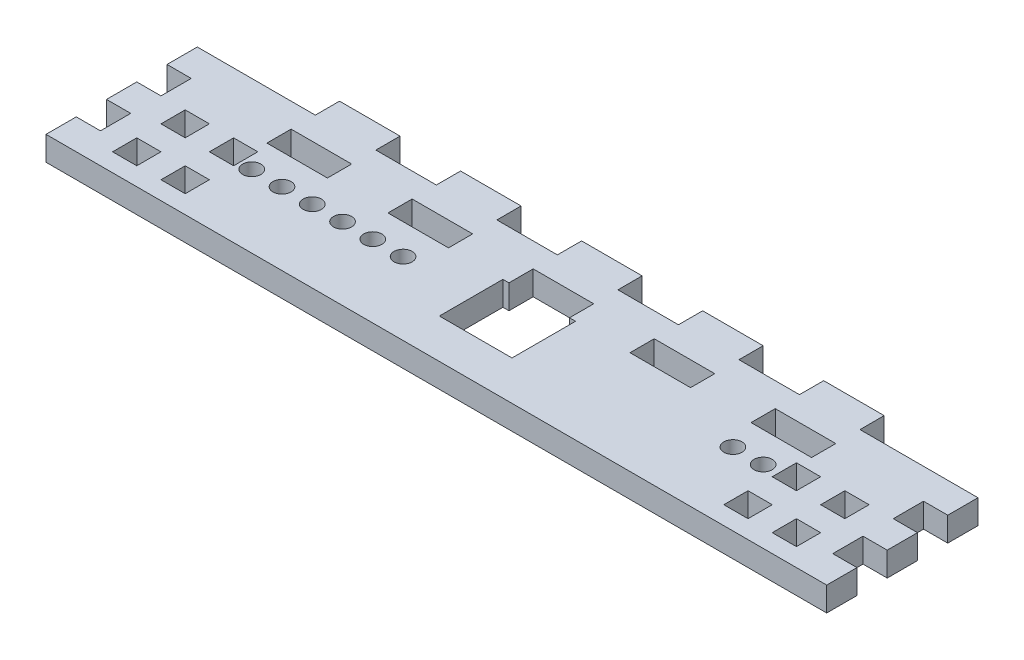
SolidWorks part; units mm, degrees
material "Maple"
ref_plane "Front Plane" through (0, 0, 0) normal (0, 0, 1) x (1, 0, 0)
ref_plane "Top Plane" through (0, 0, 0) normal (0, 1, 0) x (1, 0, 0)
ref_plane "Right Plane" through (0, 0, 0) normal (1, 0, 0) x (0, 0, -1)
sketch "Sketch1" plane through (0, 0, 0) normal (0, 1, 0) x (1, 0, 0)
  line L1 (0, 0) -> (121, 0)
  line L2 (0, 0) -> (0, -25)
  line L3 (0, -25) -> (121, -25)
  line L4 (121, 0) -> (121, -25)
  dimension "D1" = 121
  dimension "D2" = 25
extrude "Boss-Extrude1" add sketch "Sketch1" along normal blind 4
sketch "Sketch2" plane through (0, 0, 0) normal (0, -1, 0) x (-1, 0, 0)
  line L0 (0, 0) -> (0, -25) construction
  line L1 (0, -25) -> (4, -25)
  line L2 (0, -25) -> (0, -20)
  line L3 (0, -20) -> (4, -20)
  line L4 (4, -25) -> (4, -20)
  line L5 (-121, -25) -> (-125, -25)
  line L6 (-121, -25) -> (-121, -20)
  line L7 (-121, -20) -> (-125, -20)
  line L8 (-125, -25) -> (-125, -20)
  line L9 (0, -25) -> (-121, -25) construction
  dimension "D1" = 4
  dimension "D2" = 5
extrude "Boss-Extrude2" add sketch "Sketch2" against normal through all
pattern_linear "LPattern1" count 3 spacing 10 along (0, 0, -1) of "Boss-Extrude2"
sketch "Sketch3" plane through (0, 0, 0) normal (0, -1, 0) x (-1, 0, 0)
  line L0 (-60.5, -25) -> (-60.5, 0) construction
  line L1 (4, -25) -> (-125, -25) construction
  line L2 (-125, 0) -> (4, 0) construction
  line L4 (-55.5, 4) -> (-65.5, 4)
  line L5 (-55.5, 4) -> (-55.5, 0)
  line L6 (-55.5, 0) -> (-65.5, 0)
  line L7 (-65.5, 4) -> (-65.5, 0)
  line L8 (-55.5, 4) -> (-65.5, 0) construction
  line L9 (-55.5, 0) -> (-65.5, 4) construction
  point P6 (-60.5, 2)
  dimension "D1" = 4
  dimension "D2" = 10
extrude "Boss-Extrude3" add sketch "Sketch3" against normal through all
pattern_linear "LPattern2" count 3 spacing 20 along (1, 0, 0) count 3 spacing 20 along (-1, 0, 0) of "Boss-Extrude3"
sketch "Sketch4" plane through (0, 0, 0) normal (0, -1, 0) x (1, 0, 0)
  line L0 (60.5, -4) -> (60.5, 25) construction
  line L1 (15.5, 8) -> (25.5, 8)
  line L2 (15.5, 8) -> (15.5, 4)
  line L3 (15.5, 4) -> (25.5, 4)
  line L4 (25.5, 8) -> (25.5, 4)
  line L5 (35.5, 8) -> (45.5, 8)
  line L6 (35.5, 8) -> (35.5, 4)
  line L7 (35.5, 4) -> (45.5, 4)
  line L8 (45.5, 8) -> (45.5, 4)
  line L9 (55.5, 8) -> (65.5, 8)
  line L10 (55.5, 8) -> (55.5, 4)
  line L11 (55.5, 4) -> (65.5, 4)
  line L12 (65.5, 8) -> (65.5, 4)
  line L13 (75.5, 8) -> (85.5, 8)
  line L14 (75.5, 8) -> (75.5, 4)
  line L15 (75.5, 4) -> (85.5, 4)
  line L16 (85.5, 8) -> (85.5, 4)
  line L17 (95.5, 8) -> (105.5, 8)
  line L18 (95.5, 8) -> (95.5, 4)
  line L19 (95.5, 4) -> (105.5, 4)
  line L20 (105.5, 8) -> (105.5, 4)
  line L21 (55.5, -4) -> (65.5, -4) construction
  line L22 (-4, 25) -> (125, 25) construction
  dimension "D2" = 4
  dimension "D3" = 10
  dimension "D4" = 5
  dimension "D5" = 10
  dimension "D6" = 10
  dimension "D7" = 10
  dimension "D8" = 10
  dimension "D1" = 17
extrude "Cut-Extrude1" cut sketch "Sketch4" against normal through all
sketch "Sketch5" plane through (0, 4, 0) normal (0, 1, 0) x (1, 0, 0)
  line L0 (60.5, -25) -> (60.5, 4) construction
  line L1 (-4, -25) -> (125, -25) construction
  line L2 (55.5, 4) -> (65.5, 4) construction
  line L3 (121, -10) -> (121, -5) construction
  line L4 (54.5, -8) -> (66.5, -8)
  line L5 (54.5, -8) -> (54.5, -18.5)
  line L6 (54.5, -18.5) -> (66.5, -18.5)
  line L7 (66.5, -8) -> (66.5, -18.5)
  line L8 (54.5, -8) -> (66.5, -18.5) construction
  line L9 (54.5, -18.5) -> (66.5, -8) construction
  line L10 (0, -5) -> (0, -10) construction
  line L11 (105.5, -8) -> (95.5, -8) construction
  line L13 (55.5, -4) -> (65.5, -4) construction
  circle A0 centre (97.5, -13) radius 1.5
  circle A1 centre (102.5, -13) radius 1.5
  circle A2 centre (43, -13) radius 1.5
  circle A3 centre (38, -13) radius 1.5
  circle A4 centre (33, -13) radius 1.5
  circle A5 centre (28, -13) radius 1.5
  circle A6 centre (23, -13) radius 1.5
  circle A7 centre (18, -13) radius 1.5
  point P6 (60.5, -13.25)
  dimension "D4" = 3
  dimension "D5" = 3
  dimension "D1" = 10.5
  dimension "D2" = 12
  dimension "D6" = 5
  dimension "D8" = 18.5
  dimension "D9" = 5
  dimension "D10" = 5
  dimension "D11" = 5
  dimension "D12" = 5
  dimension "D13" = 5
  dimension "D14" = 18
  dimension "D7" = 5
  dimension "D3" = 4
extrude "Cut-Extrude2" cut sketch "Sketch5" against normal through all
sketch "Sketch6" [suppressed] plane through (0, 0, 0) normal (0, -1, 0) x (1, 0, 0)
  line L0 (45.5, 8) -> (35.5, 8) construction
  line L1 (-4, 13) -> (125, 13) construction
  line L2 (-4, 15) -> (-4, 10) construction
  line L3 (125, 10) -> (125, 15) construction
  circle A0 centre (38, 13) radius 1.5
  circle A1 centre (33, 13) radius 1.5
  circle A5 centre (28, 13) radius 1.5
  circle A6 centre (23, 13) radius 1.5
  circle A7 centre (18, 13) radius 1.5
  circle A9 centre (84, 13) radius 1.5
  circle A10 centre (89, 13) radius 1.5
  circle A11 centre (95.5, 13) radius 1.5
  circle A12 centre (100.5, 13) radius 1.5
  circle A13 centre (105.5, 13) radius 1.5
  dimension "D6" = 5
  dimension "D9" = 5
  dimension "D10" = 5
  dimension "D11" = 5
  dimension "D1" = 3
  dimension "D2" = 5
  dimension "D3" = 5
  dimension "D4" = 5
  dimension "D5" = 5
  dimension "D12" = 19.5
  dimension "D13" = 36
  dimension "D7" = 22
extrude "Cut-Extrude3" [suppressed] cut sketch "Sketch6" against normal through all
sketch "Sketch7" plane through (0, 0, 0) normal (0, -1, 0) x (1, 0, 0)
  line L0 (-4, 25) -> (125, 25) construction
  line L1 (4, 22) -> (8, 22)
  line L2 (4, 22) -> (4, 18)
  line L3 (4, 18) -> (8, 18)
  line L4 (8, 22) -> (8, 18)
  line L5 (12, 22) -> (16, 22)
  line L6 (12, 22) -> (12, 18)
  line L7 (12, 18) -> (16, 18)
  line L8 (16, 22) -> (16, 18)
  line L9 (4, 14) -> (8, 14)
  line L10 (4, 14) -> (4, 10)
  line L11 (4, 10) -> (8, 10)
  line L12 (8, 14) -> (8, 10)
  line L13 (12, 14) -> (16, 14)
  line L14 (12, 14) -> (12, 10)
  line L15 (12, 10) -> (16, 10)
  line L16 (16, 14) -> (16, 10)
  line L17 (105, 22) -> (109, 22)
  line L18 (105, 22) -> (105, 18)
  line L19 (105, 18) -> (109, 18)
  line L20 (109, 22) -> (109, 18)
  line L21 (105, 14) -> (109, 14)
  line L22 (105, 14) -> (105, 10)
  line L23 (105, 10) -> (109, 10)
  line L24 (109, 14) -> (109, 10)
  line L25 (113, 22) -> (117, 22)
  line L26 (113, 22) -> (113, 18)
  line L27 (113, 18) -> (117, 18)
  line L28 (117, 22) -> (117, 18)
  line L29 (113, 14) -> (117, 14)
  line L30 (113, 14) -> (113, 10)
  line L31 (113, 10) -> (117, 10)
  line L32 (117, 14) -> (117, 10)
  line L33 (-4, 25) -> (-4, 20) construction
  line L34 (125, 20) -> (125, 25) construction
  dimension "D1" = 3
  dimension "D2" = 8
  dimension "D3" = 4
  dimension "D4" = 4
  dimension "D5" = 4
  dimension "D6" = 4
  dimension "D7" = 4
  dimension "D8" = 8
  dimension "D9" = 4
  dimension "D10" = 4
  dimension "D11" = 4
extrude "Cut-Extrude4" cut sketch "Sketch7" against normal through all
equation "\"D5@Sketch5\"=\"D4@Sketch5\""
equation "\"D10@Sketch5\"=\"D9@Sketch5\""
equation "\"D11@Sketch5\"=\"D9@Sketch5\""
equation "\"D12@Sketch5\"=\"D9@Sketch5\""
equation "\"D13@Sketch5\"=\"D9@Sketch5\""
equation "\"D6@Sketch4\"=\"D5@Sketch4\""
equation "\"D7@Sketch4\"=\"D5@Sketch4\""
equation "\"D8@Sketch4\"=\"D5@Sketch4\""
equation "\"D5@Sketch6\"=\"D3@Sketch6\""
equation "\"D4@Sketch6\"=\"D3@Sketch6\""
equation "\"D6@Sketch6\"=\"D3@Sketch6\""
equation "\"D9@Sketch6\"=\"D3@Sketch6\""
equation "\"D10@Sketch6\"=\"D3@Sketch6\""
equation "\"D11@Sketch6\"=\"D3@Sketch6\""
